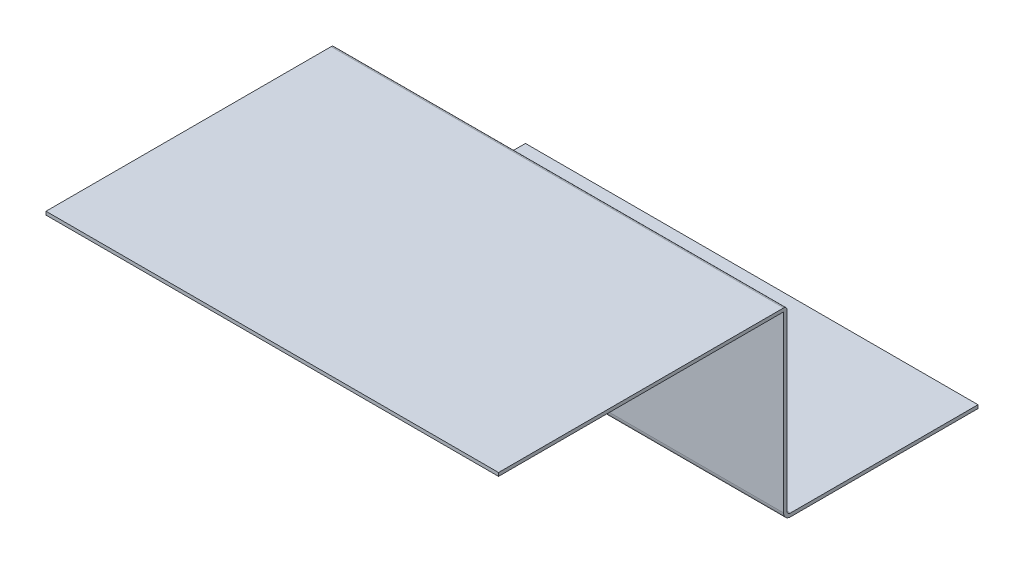
SolidWorks part; units mm, degrees
material "201 Acero inoxidable recocido (SS)"
ref_plane "Alzado" through (0, 0, 0) normal (0, 0, 1) x (1, 0, 0)
ref_plane "Planta" through (0, 0, 0) normal (0, 1, 0) x (1, 0, 0)
ref_plane "Vista lateral" through (0, 0, 0) normal (1, 0, 0) x (0, 0, -1)
sketch "Croquis1" plane through (0, 0, 0) normal (1, 0, 0) x (0, 0, -1)
  line L0 (-3, 0) -> (-255, 0)
  line L1 (0, -3) -> (0, -157)
  line L2 (3, -160) -> (168.8, -160)
  line L3 (3, -163) -> (168.8, -163)
  line L4 (-3, -3) -> (-3, -157)
  line L5 (-3, -3) -> (-255, -3)
  line L6 (168.8, -160) -> (168.8, -163)
  line L7 (-255, 0) -> (-255, -3)
  arc A0 (3, -160) -> (0, -157) centre (3, -157) cw
  arc A1 (0, -3) -> (-3, 0) centre (-3, -3) ccw
  arc A2 (3, -163) -> (-3, -157) centre (3, -157) cw
  arc A3 (-3, -3) -> (-3, -3) centre (-3, -3) ccw
  point P7 (0, -160)
  point P10 (0, 0)
  dimension "D4" = 3
  dimension "D1" = 255
  dimension "D2" = 160
  dimension "D3" = 168.8
  dimension "D5" = 3
extrude "Saliente-Extruir1" add sketch "Croquis1" along normal blind 400
